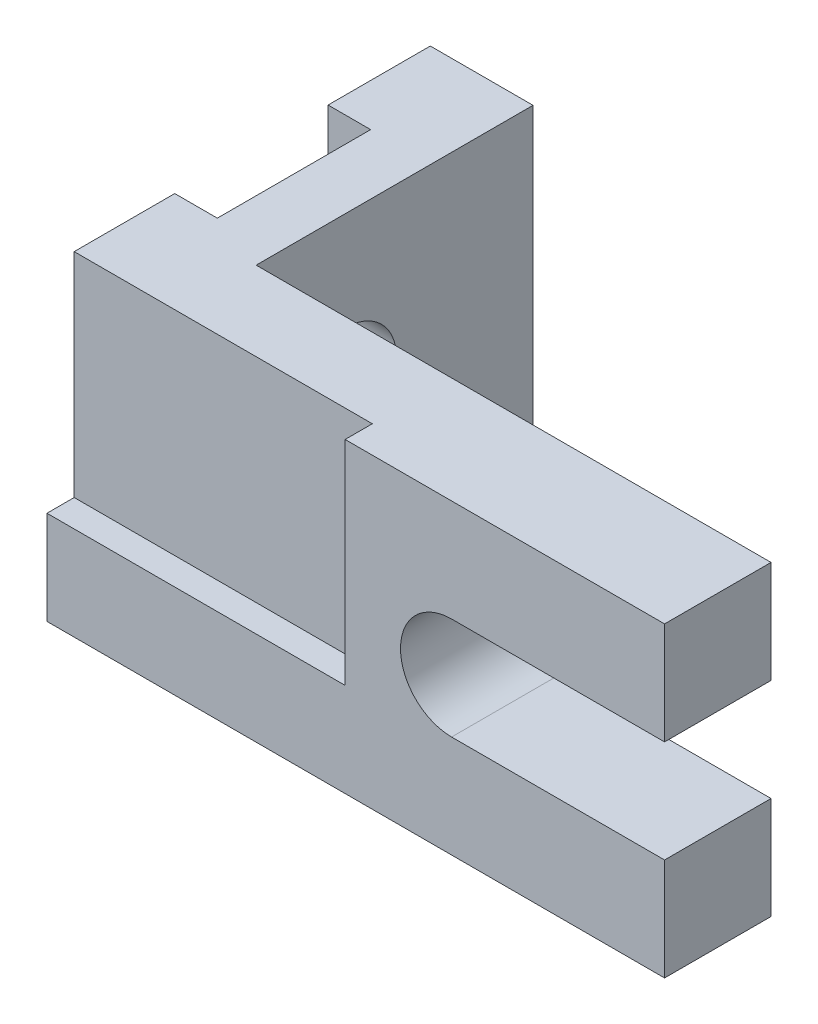
SolidWorks part; units mm, degrees
ref_plane "Front Plane" through (0, 0, 0) normal (0, 0, 1) x (1, 0, 0)
ref_plane "Top Plane" through (0, 0, 0) normal (0, 1, 0) x (1, 0, 0)
ref_plane "Right Plane" through (0, 0, 0) normal (1, 0, 0) x (0, 0, -1)
sketch "Sketch1" plane through (0, 0, 0) normal (0, 0, 1) x (1, 0, 0)
  line L1 (0, 0) -> (145, 0)
  line L2 (0, 0) -> (0, 72)
  line L3 (0, 72) -> (145, 72)
  line L4 (145, 0) -> (145, 72)
  dimension "D1" = 145
  dimension "D2" = 72
extrude "Boss-Extrude1" add sketch "Sketch1" along normal blind 25
sketch "Sketch5" plane through (0, 72, 0) normal (0, 1, 0) x (1, 0, 0)
  line L0 (0, 0) -> (0, 65)
  line L1 (0, 65) -> (24.1155, 65)
  line L2 (24.1155, 65) -> (24.1155, 0)
  line L3 (145, 0) -> (0, 0) construction
  line L4 (1.7987, 0) -> (24.1155, 0)
  line L8 (145, 0) -> (0, 0)
  line L9 (0, 0) -> (0, -25)
  line L10 (0, -25) -> (145, -25)
  line L11 (145, -25) -> (145, 0)
  line L12 (145, 0) -> (24.1155, 0)
  line L13 (0, 0) -> (0, -25)
  line L14 (0, -25) -> (145, -25)
  line L15 (145, -25) -> (145, 0)
  line M8 (145, 0) -> (0, 0)
  dimension "D1" = 90
  dimension "D2" = 0
extrude "Boss-Extrude13" add sketch "Sketch5" against normal blind 72 contours L2 L1 L0 M8
sketch "Sketch16" plane through (0, 0, 0) normal (-1, 0, 0) x (0, 0, 1)
  line L0 (25, 36) -> (-65, 36) construction
  line L1 (25, 72) -> (25, 0) construction
  line L2 (-65, 0) -> (-65, 72) construction
  line L3 (-20, 72) -> (-20, 0) construction
  line L4 (25, 72) -> (-65, 72) construction
  line L5 (25, 0) -> (-65, 0) construction
  line L6 (-41, 72) -> (-41, 0)
  line L7 (-5, 72) -> (-5, 0)
  circle A0 centre (-20, 36) radius 30
  circle A1 centre (-20, 36) radius 12
  line M3 (25, 72) -> (-65, 72)
  line M5 (-65, 0) -> (25, 0)
  dimension "D2" = 24
  dimension "D3" = 60
  dimension "D1" = 45
  dimension "D4" = 24
  dimension "D5" = 30
extrude "Cut-Extrude1" cut sketch "Sketch16" against normal blind 10 contours L7 A0 L6 A1 | A1 | L7 A0 | L6 A0 | A0 L7 L6 M3 | A0 L6 L7 M5
sketch "Sketch17" plane through (0, 72, 0) normal (0, 1, 0) x (1, 0, 0)
  line L0 (70, -18.6098) -> (70, -25)
  line L1 (145, -25) -> (0, -25) construction
  line L2 (70, -18.6098) -> (0, -18.6098)
  line L3 (0, -25) -> (0, 5) construction
  dimension "D1" = 70
extrude "Cut-Extrude2" cut sketch "Sketch17" against normal blind 50 and the other way through all
sketch "Sketch18" plane through (10, 0, 0) normal (-1, 0, 0) x (0, 0, 1)
  circle A0 centre (-20.9422, 36.7851) radius 12
  dimension "D1" = 24
extrude "Cut-Extrude3" cut sketch "Sketch18" against normal blind 24 contours A0
sketch "Sketch19" plane through (0, 0, 0) normal (0, 0, -1) x (-1, 0, 0)
  line L0 (-95, 36) -> (-145, 36) construction
  line L1 (-145, 0) -> (-145, 72) construction
  line L2 (-95, 24) -> (-145, 24)
  line L3 (-95, 48) -> (-145, 48)
  arc A0 (-95, 24) -> (-95, 48) centre (-95, 36) ccw
  point P4 (-120, 36)
  dimension "D1" = 12
  dimension "D2" = 12
  dimension "D3" = 50
  dimension "D4" = 24
extrude "Cut-Extrude4" cut sketch "Sketch19" against normal blind 25 and the other way through all
